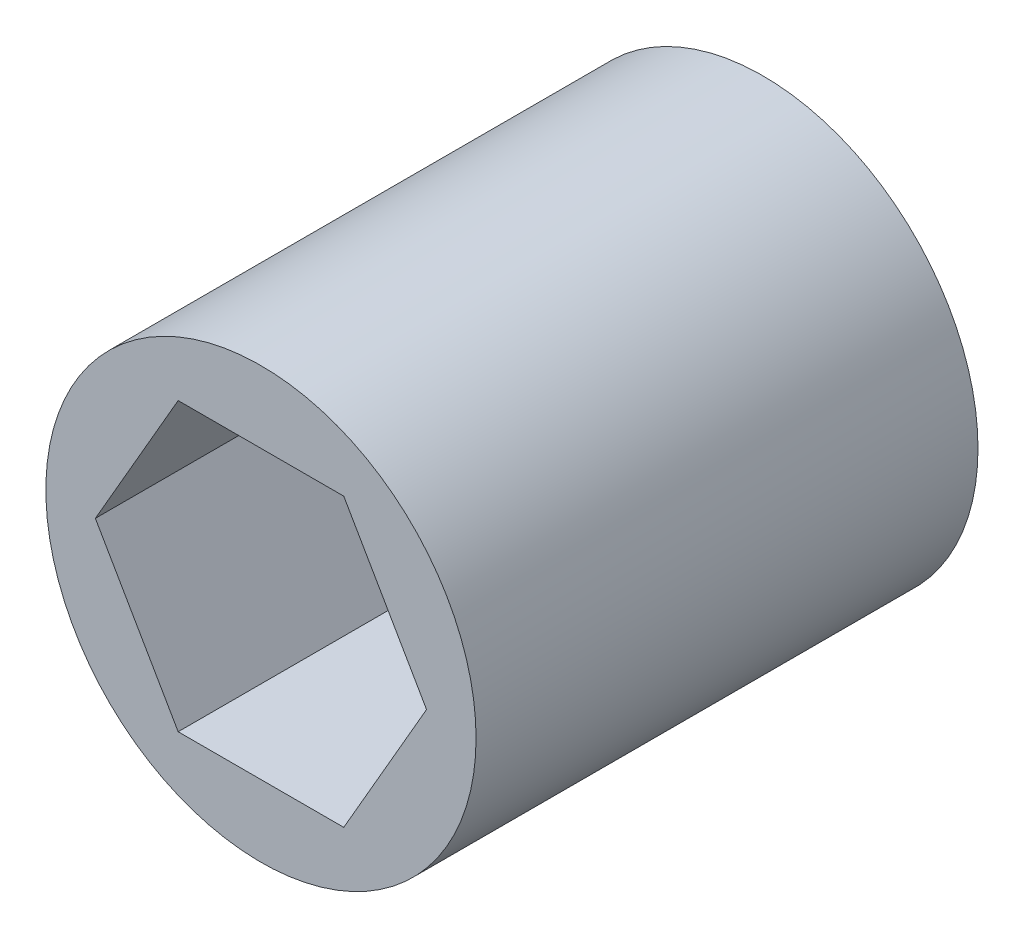
SolidWorks part; units mm, degrees
material "Nylon 101"
ref_plane "Front Plane" through (0, 0, 0) normal (0, 0, 1) x (1, 0, 0)
ref_plane "Top Plane" through (0, 0, 0) normal (0, 1, 0) x (1, 0, 0)
ref_plane "Right Plane" through (0, 0, 0) normal (1, 0, 0) x (0, 0, -1)
sketch "Sketch1" plane through (0, 0, 0) normal (0, 0, 1) x (1, 0, 0)
  line L1 (-3.6662, 6.35) -> (-7.3323, 0)
  line L2 (-7.3323, 0) -> (-3.6662, -6.35)
  line L3 (-3.6662, -6.35) -> (3.6662, -6.35)
  line L4 (3.6662, -6.35) -> (7.3323, 0)
  line L5 (7.3323, 0) -> (3.6662, 6.35)
  line L6 (3.6662, 6.35) -> (-3.6662, 6.35)
  circle A0 centre (0, 0) radius 6.35 construction
  circle A1 centre (0, 0) radius 9.525
  point P10 (0, 6.35)
  dimension "D1" = 12.7
  dimension "D2" = 19.05
extrude "Boss-Extrude1" add sketch "Sketch1" along normal blind 22.225
